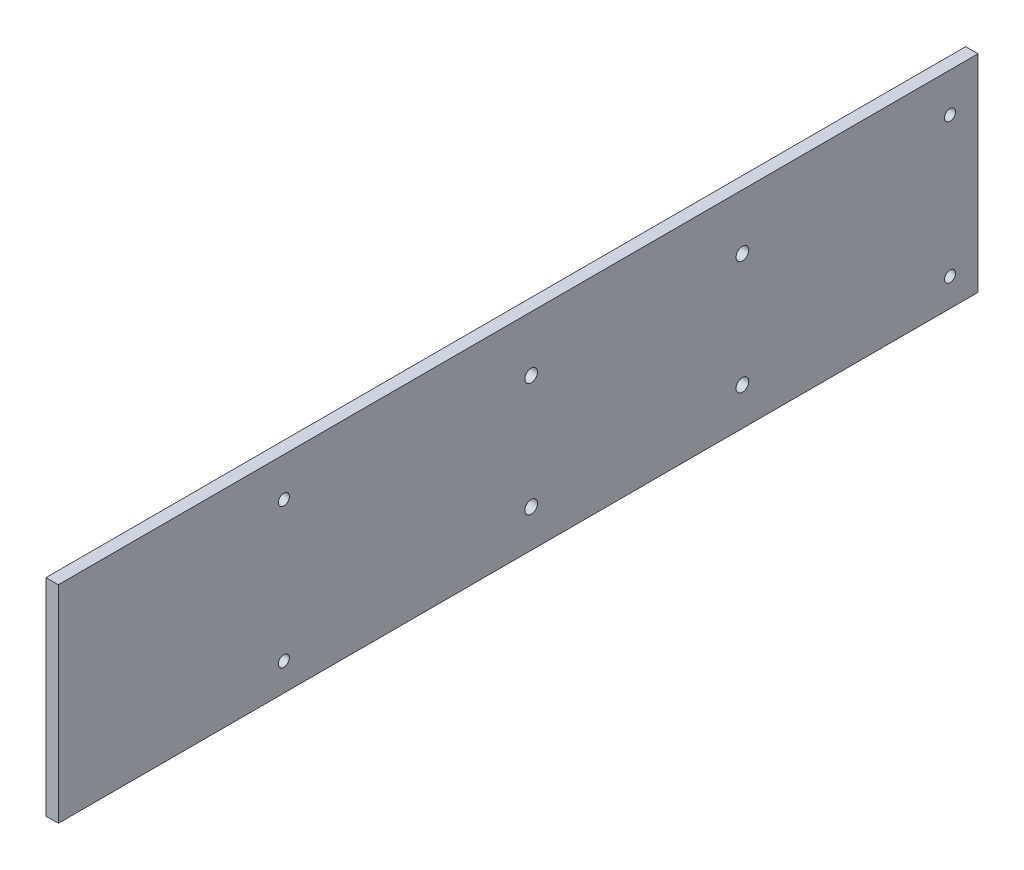
SolidWorks part; units mm, degrees
material "6061-T6 (SS)"
ref_plane "Front Plane" through (0, 0, 0) normal (0, 0, 1) x (1, 0, 0)
ref_plane "Top Plane" through (0, 0, 0) normal (0, 1, 0) x (1, 0, 0)
ref_plane "Right Plane" through (0, 0, 0) normal (1, 0, 0) x (0, 0, -1)
sketch "Sketch1" plane through (0, 0, 0) normal (1, 0, 0) x (0, 0, -1)
  line L1 (-179.705, 38.1) -> (179.705, 38.1)
  line L2 (-179.705, 38.1) -> (-179.705, -38.1)
  line L3 (-179.705, -38.1) -> (179.705, -38.1)
  line L4 (179.705, 38.1) -> (179.705, -38.1)
  line L5 (-179.705, 38.1) -> (179.705, -38.1) construction
  line L6 (-179.705, -38.1) -> (179.705, 38.1) construction
  point P0 (0, 0)
  dimension "D1" = 76.2
  dimension "D2" = 359.41
extrude "Boss-Extrude1" add sketch "Sketch1" along normal blind 4.826
sketch "Sketch2" plane through (4.826, 0, 0) normal (1, 0, 0) x (0, 0, -1)
  line L0 (179.705, -38.1) -> (179.705, 38.1) construction
  line L1 (-91.567, 22.86) -> (168.783, 22.86) construction
  line L2 (-91.567, 22.86) -> (-91.567, -31.75) construction
  line L3 (-91.567, -31.75) -> (168.783, -31.75) construction
  line L4 (168.783, 22.86) -> (168.783, -31.75) construction
  line L5 (-91.567, 22.86) -> (168.783, -31.75) construction
  line L6 (-91.567, -31.75) -> (168.783, 22.86) construction
  line L7 (-179.705, 38.1) -> (-179.705, -38.1) construction
  line L8 (5.08, -27.94) -> (87.63, -27.94) construction
  line L9 (-179.705, -38.1) -> (179.705, -38.1) construction
  line L11 (5.08, -27.94) -> (87.63, -27.94) construction
  line L12 (5.08, -27.94) -> (5.08, 16.51) construction
  line L13 (5.08, 16.51) -> (87.63, 16.51) construction
  line L14 (87.63, -27.94) -> (87.63, 16.51) construction
  point P0 (38.608, -4.445)
  point P7 (0, 0)
  point P17 (-174.498, 4.0792)
  point P18 (-162.941, -2.413)
  dimension "D1" = 10.922
  dimension "D2" = 260.35
  dimension "D3" = 54.61
  dimension "D4" = 10.16
  dimension "D5" = 82.55
  dimension "D6" = 92.075
  dimension "D7" = 44.45
  dimension "D8" = 5.207
  dimension "D9" = 42.1792
  dimension "D10" = 6.35
  dimension "D11" = 35.687
  dimension "D12" = 16.764
hole_wizard "#10 Clearance Hole1" positions "Sketch3" profile "Sketch4" hole size "#10" standard "ANSI Inch" end condition through all
sketch "Sketch3" plane through (4.826, 0, 0) normal (1, 0, 0) x (0, 0, -1)
  point P12 (87.63, -27.94)
  point P15 (5.08, -27.94)
  point P18 (5.08, 16.51)
  point P21 (87.63, 16.51)
sketch "Sketch4" plane through (4.826, -27.94, -87.63) normal (0, 1, 0) x (0, 0, -1)
  line L0 (0, 0) -> (0, 4.826)
  line L1 (0, 4.826) -> (2.4892, 4.826)
  line L2 (2.4892, 4.826) -> (2.4892, 0)
  line L5 (2.4892, 0) -> (0, 0)
  line L11 (0, -6.35) -> (0, 107.95) construction
  dimension "Thru Hole Dia." = 4.9784
  dimension "Thru Hole Depth" = 4.826
hole_wizard "#8 Clearance Hole1" positions "Sketch17" profile "Sketch18" hole size "#8" standard "ANSI Inch"
sketch "Sketch17" plane through (4.826, 0, 0) normal (1, 0, 0) x (0, 0, -1)
  point P3 (-91.567, 22.86)
  point P6 (-91.567, -31.75)
  point P9 (168.783, -31.75)
  point P12 (168.783, 22.86)
sketch "Sketch18" plane through (4.826, 22.86, 91.567) normal (0, 1, 0) x (0, 0, -1)
  line L0 (0, 0) -> (0, 13.9934)
  line L1 (0, 13.9934) -> (2.1526, 12.7)
  line L2 (2.1526, 12.7) -> (2.1526, 0)
  line L5 (2.1526, 0) -> (0, 0)
  line L10 (0, 13.9934) -> (-2.1527, 12.7) construction
  line L11 (0, -6.35) -> (0, 107.95) construction
  dimension "Hole Dia." = 4.3053
  dimension "Hole Depth" = 12.7
  dimension "Drill Angle" = 118
sketch "Sketch31" plane through (0, -38.1, 0) normal (0, -1, 0) x (1, 0, 0)
  line L1 (4.826, 179.705) -> (0, 179.705)
  line L2 (4.826, 179.705) -> (4.826, -179.705)
  line L3 (4.826, -179.705) -> (0, -179.705)
  line L4 (0, 179.705) -> (0, -179.705)
extrude "Boss-Extrude10" add sketch "Sketch31" along normal blind 4.572
sketch "Sketch5" plane through (4.826, 0, 0) normal (1, 0, 0) x (0, 0, -1)
  circle A0 centre (-91.567, 22.86) radius 6.35
  circle A1 centre (-91.567, -31.75) radius 6.35
  circle A2 centre (168.783, 22.86) radius 6.35
  circle A3 centre (168.783, -31.75) radius 6.35
  circle A4 centre (87.63, -27.94) radius 6.35
  circle A5 centre (5.08, -27.94) radius 6.35
  circle A6 centre (5.08, 16.51) radius 6.35
  circle A7 centre (87.63, 16.51) radius 6.35
  circle A8 centre (-174.498, 4.0792) radius 4.7625
  circle A9 centre (-162.941, -2.413) radius 3.2639
  circle A10 centre (-162.941, -2.413) radius 6.4158
  circle A11 centre (-174.498, 4.0792) radius 2.0098
  dimension "D4" = 12.7
  dimension "D2" = 9.525
  dimension "D3" = 6.5278
  dimension "D5" = 12.8316
  dimension "D6" = 4.0196
